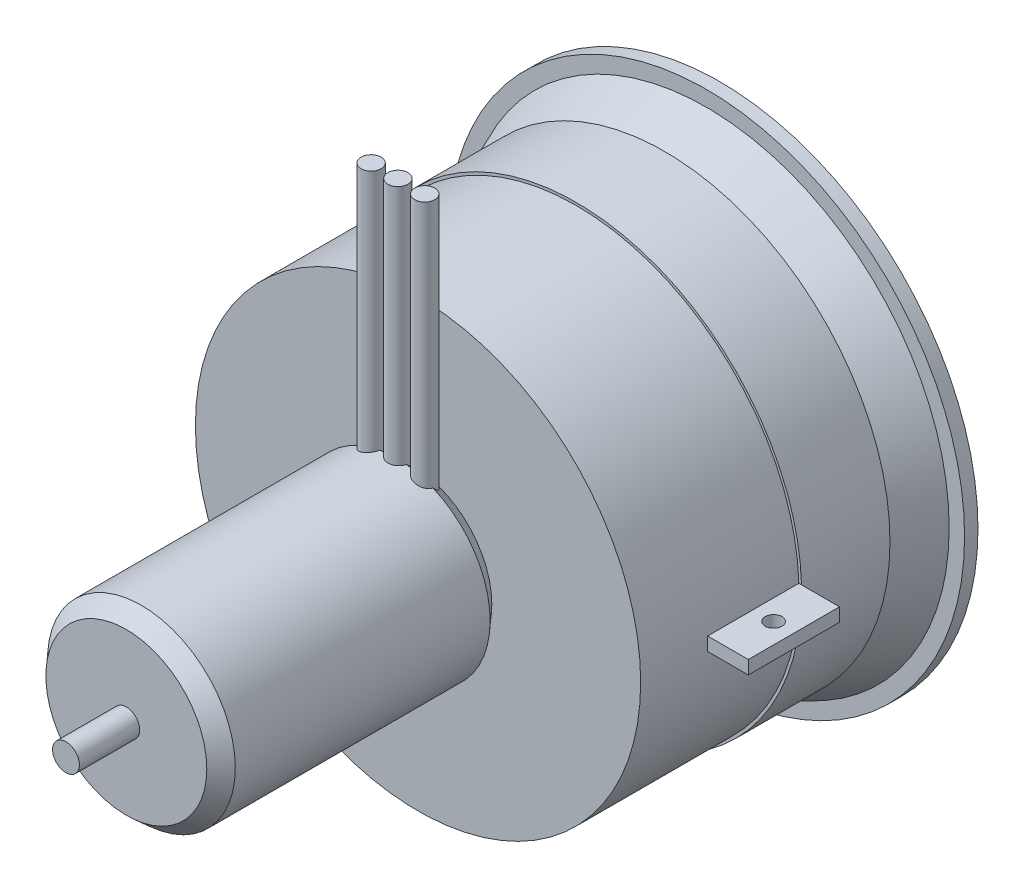
SolidWorks part; units mm, degrees
ref_plane "Front Plane" through (0, 0, 0) normal (1, 0, 0) x (0, 1, 0)
ref_plane "Top Plane" through (0, 0, 0) normal (0, 0, 1) x (0, 1, 0)
ref_plane "Right Plane" through (0, 0, 0) normal (0, 1, 0) x (-1, 0, 0)
sketch "Sketch1" plane through (0, 0, 0) normal (1, 0, 0) x (0, 1, 0)
  line L0 (0, 0) -> (0, -32.442) construction
  line L1 (0, 0) -> (38.5, 0)
  line L2 (38.5, 0) -> (38.5, 2)
  line L3 (38.5, 2) -> (36.2, 2)
  line L4 (36.2, 2) -> (33.6, 8.225)
  line L5 (33.6, 8.225) -> (33.6, 21.4)
  line L6 (33.2, 21.4) -> (33.2, 45)
  line L7 (33.2, 45) -> (5, 45)
  line L9 (5, 46) -> (12, 46)
  line L10 (12, 46) -> (14, 48.25)
  line L11 (14, 48.25) -> (14, 86.25)
  line L12 (14, 86.25) -> (12, 88.5)
  line L13 (12, 88.5) -> (2, 88.5)
  line L14 (2, 88.5) -> (2, 97.5)
  line L15 (2, 97.5) -> (0, 97.5)
  line L17 (33.2, 21.4) -> (33.6, 21.4)
  line L19 (0, 97.5) -> (0, 0)
  line L20 (5, 46) -> (5, 45)
  dimension "D1" = 77
  dimension "D2" = 72.4
  dimension "D3" = 67.2
  dimension "D4" = 66.4
  dimension "D5" = 45
  dimension "D6" = 23.6
  dimension "D7" = 97.5
  dimension "D8" = 2
  dimension "D9" = 4
  dimension "D10" = 28
  dimension "D11" = 1
  dimension "D12" = 42.5
  dimension "D13" = 10
  dimension "D14" = 10
  dimension "D15" = 38
revolve "Revolve1" add sketch "Sketch1" angle 360 about L0
sketch "Sketch3" plane through (0, 0, 0) normal (1, 0, 0) x (0, 1, 0)
  line L0 (33.2, 45) -> (-33.2, 45) construction
  line L1 (-1, 35) -> (1, 35)
  line L2 (-1, 35) -> (-1, 21.4)
  line L3 (-1, 21.4) -> (1, 21.4)
  line L4 (1, 35) -> (1, 21.4)
  point P4 (0, 21.4)
  dimension "D1" = 13.6
  dimension "D2" = 10
  dimension "D3" = 2
extrude "Boss-Extrude1" add sketch "Sketch3" along normal mid plane 78.5
sketch "Sketch4" plane through (0, 1, 0) normal (0, 1, 0) x (-1, 0, 0)
  line L0 (-39.25, 35) -> (-33.1849, 35) construction
  line L1 (-39.25, 28.2) -> (-33.1849, 28.2) construction
  line L4 (-39.25, 21.4) -> (-39.25, 35) construction
  line L5 (-33.1849, 21.4) -> (-33.1849, 35) construction
  circle A0 centre (-36.2175, 28.2) radius 1.25
  dimension "D2" = 2.5
  dimension "D1" = 6.8
extrude "Cut-Extrude1" cut sketch "Sketch4" against normal through all
mirror "Mirror1" about plane through (0, 0, 0) normal (1, 0, 0) of "Cut-Extrude1"
sketch "Sketch5" plane through (0, 0, 0) normal (0, 1, 0) x (-1, 0, 0)
  line L2 (-12, 46) -> (12, 46) construction
  circle A0 centre (0, 48) radius 1.5
  circle A1 centre (4, 48) radius 1.5
  circle A2 centre (-4, 48) radius 1.5
  dimension "D1" = 3
  dimension "D2" = 0.5
  dimension "D3" = 1
  dimension "D4" = 1
extrude "Boss-Extrude5" add sketch "Sketch5" along normal blind 50
